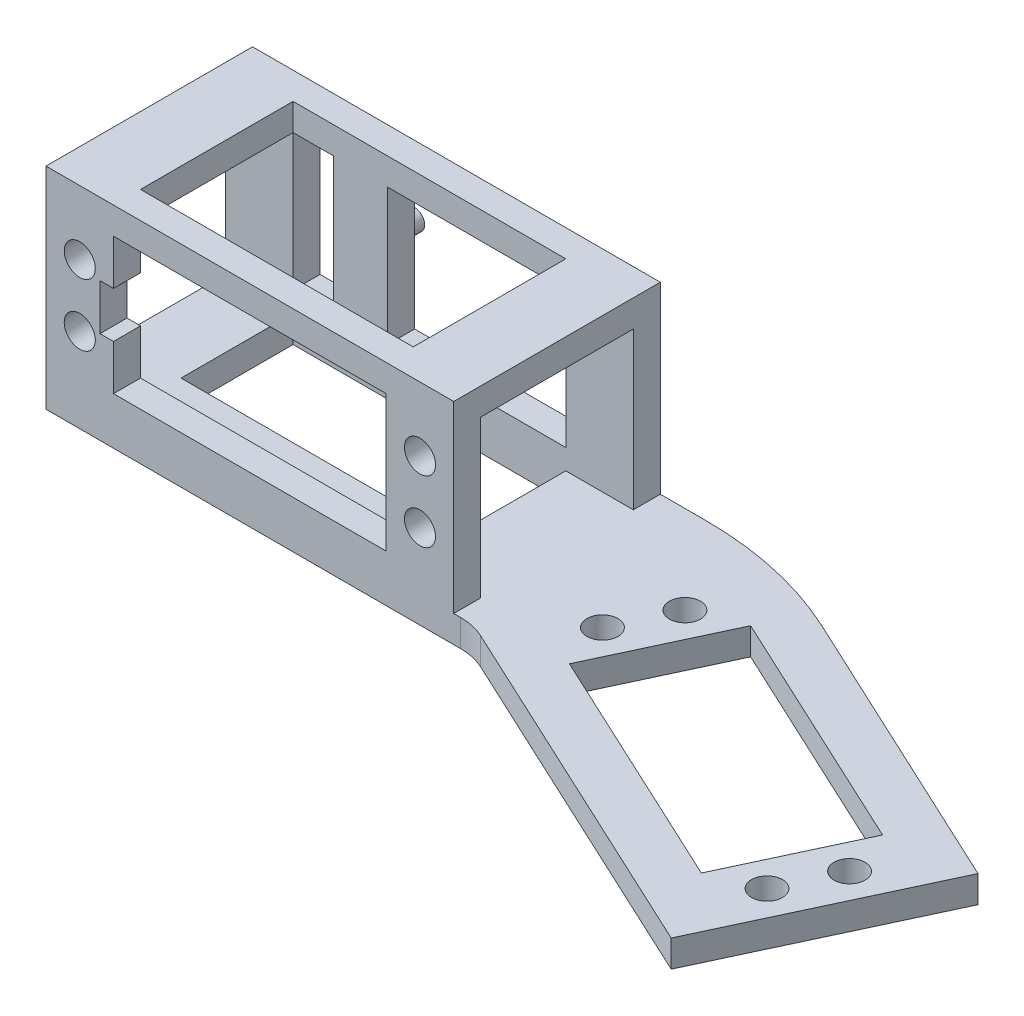
SolidWorks part; units mm, degrees
ref_plane "Płaszczyzna przednia" through (0, 0, 0) normal (0, 0, 1) x (1, 0, 0)
ref_plane "Płaszczyzna górna" through (0, 0, 0) normal (0, 1, 0) x (1, 0, 0)
ref_plane "Płaszczyzna prawa" through (0, 0, 0) normal (1, 0, 0) x (0, 0, -1)
sketch "Szkic1" plane through (0, 0, 0) normal (0, 0, 1) x (1, 0, 0)
  line L0 (17.1567, 10.1) -> (79.0535, 10.1) construction
  line L9 (-10, 27.2) -> (50.4, 27.2)
  line L10 (-10, 27.2) -> (-10, -7)
  line L11 (-10, -7) -> (50.4, -7)
  line L12 (50.4, 27.2) -> (50.4, -7)
  line L13 (20.2, 34.0981) -> (20.2, -18.6436) construction
extrude "Dodanie-wyciągnięcie1" add sketch "Szkic1" along normal blind 4
sketch "Szkic2" plane through (0, -7, 0) normal (0, -1, 0) x (1, 0, 0)
  line L1 (-10, 4) -> (-10, 0)
  line L2 (-10, 0) -> (-16.7213, 0)
  line L6 (50.4, 4) -> (50.4, 30.6)
  line L7 (50.4, 30.6) -> (-10, 30.6)
  line L9 (-10, 4) -> (50.4, 4) construction
  line L10 (-10, 4) -> (0, 4)
  line L11 (40.4, 4) -> (40.4, 20.6)
  line L12 (40.4, 20.6) -> (0, 20.6)
  line L13 (0, 20.6) -> (0, 4)
  line L14 (40.4, 4) -> (50.4, 4)
  line L16 (-38.789, 4.8923) -> (-82.1898, 25.1304)
  line L24 (50.4, 4) -> (50.4, 0) construction
  line L25 (-10, 30.6) -> (-11, 30.6)
  line L26 (-14.8036, 31.4432) -> (-67.7362, 56.1261)
  line L27 (-67.7362, 56.1261) -> (-82.1898, 25.1304)
  line L28 (-61.6315, 45.5558) -> (-70.1684, 27.2484)
  line L29 (-70.1684, 27.2484) -> (-33.5535, 10.1746)
  line L30 (-33.5535, 10.1746) -> (-25.0167, 28.482)
  line L31 (-25.0167, 28.482) -> (-61.6315, 45.5558)
  line L32 (-10, 4) -> (-10, 0) construction
  line L33 (-76.5626, 25.3669) -> (-59.3874, 62.1993) construction
  line L34 (-51.861, 18.7115) -> (-32.7873, 59.6151) construction
  line L35 (-65.8999, 36.4021) -> (-24.1196, 16.9196) construction
  arc A4 (-11, 30.6) -> (-14.8036, 31.4432) centre (-11, 39.6) cw
  arc A5 (-16.7213, 0) -> (-38.789, 4.8923) centre (-16.7213, 52.2167) cw
  circle A6 centre (-68.4874, 42.6842) radius 2.3
  circle A7 centre (-22.8095, 21.3842) radius 2.3
  circle A8 centre (-26.6976, 13.0462) radius 2.3
  circle A9 centre (-72.3755, 34.3462) radius 2.3
  point P37 (-12.9953, 30.6)
  dimension "D15" = 9
  dimension "D24" = 4.6
  dimension "D6" = 52.2167
  dimension "D1" = 10
  dimension "D2" = 10
  dimension "D3" = 10
  dimension "D4" = 26.6
  dimension "D16" = 60.4
  dimension "D17" = 7
  dimension "D18" = 7
  dimension "D19" = 40.4
  dimension "D20" = 10
  dimension "D21" = 65
  dimension "D22" = 1
  dimension "D23" = 5
  dimension "D25" = 5.5
  dimension "D26" = 20.2
extrude "Dodanie-wyciągnięcie2" add sketch "Szkic2" against normal blind 4
sketch "Szkic8" plane through (0, 0, 30.6) normal (0, 0, 1) x (1, 0, 0)
  line L0 (-9.6092, 10.1) -> (52.2876, 10.1) construction
  line L1 (0, 20.2) -> (40.4, 20.2)
  line L2 (0, 20.2) -> (0, 0)
  line L3 (0, 0) -> (40.4, 0)
  line L4 (40.4, 20.2) -> (40.4, 0)
  line L5 (-10, 25.2) -> (50.4, 25.2)
  line L6 (-10, 25.2) -> (-10, -7)
  line L7 (-10, -7) -> (50.4, -7)
  line L8 (50.4, 25.2) -> (50.4, -7)
  line L9 (20.2, 34.6544) -> (20.2, -18.0872) construction
  line L10 (50.4, -7) -> (-11, -7) construction
  line L11 (50.4, -3) -> (50.4, 27.2) construction
  circle A0 centre (-5, 14.7) radius 2.3
  circle A1 centre (-5, 5.5) radius 2.3
  circle A2 centre (45.4, 5.5) radius 2.3
  circle A3 centre (45.4, 14.7) radius 2.3
  point P29 (0, 10.1)
  point P31 (20.2, 20.2)
  dimension "D8" = 4.6
  dimension "D1" = 40.4
  dimension "D2" = 20.2
  dimension "D3" = 10
  dimension "D4" = 5
  dimension "D5" = 10
  dimension "D6" = 7
  dimension "D7" = 5.5
  dimension "D9" = 5
extrude "Dodanie-wyciągnięcie3" add sketch "Szkic8" against normal blind 4
sketch "Szkic10" plane through (0, 0, 0) normal (0, 0, -1) x (-1, 0, 0)
  line L0 (-47.6229, 10.1) -> (25.9546, 10.1) construction
  line L1 (-50.4, -7) -> (-50.4, 27.2) construction
  circle A0 centre (-30.4, 10.1) radius 1.5
  point P9 (-50.4, 10.1)
  dimension "D2" = 3
  dimension "D1" = 20
extrude "Dodanie-wyciągnięcie4" add sketch "Szkic10" along normal blind 4
sketch "Szkic11" plane through (0, 27.2, 0) normal (0, 1, 0) x (1, 0, 0)
  line L0 (50.4, -30.6) -> (-10, -30.6) construction
  line L1 (-10, 0) -> (0, 0)
  line L2 (-10, 0) -> (-10, -30.6)
  line L3 (-10, -30.6) -> (0, -30.6)
  line L4 (0, 0) -> (0, -30.6)
  line L6 (50.4, 0) -> (40.4, 0)
  line L7 (50.4, 0) -> (50.4, -30.6)
  line L8 (50.4, -30.6) -> (40.4, -30.6)
  line L9 (40.4, 0) -> (40.4, -30.6)
extrude "Dodanie-wyciągnięcie5" add sketch "Szkic11" against normal blind 5 from offset 2 offset against normal yes
sketch "Szkic12" plane through (0, 27.2, 0) normal (0, 1, 0) x (1, 0, 0)
  line L1 (-10, 0) -> (50.4, 0)
  line L2 (-10, 0) -> (-10, -4)
  line L4 (50.4, 0) -> (50.4, -4)
  line L6 (-10, -4) -> (-10, -30.6)
  line L7 (-10, -30.6) -> (50.4, -30.6)
  line L8 (50.4, -4) -> (50.4, -30.6)
extrude "Wytnij-wyciągnięcie1" cut sketch "Szkic12" against normal blind 3
sketch "Szkic13" plane through (0, 0, 0) normal (0, 0, -1) x (-1, 0, 0)
  line L0 (-40.4, 20.2) -> (0, 20.2) construction
  line L1 (-40.4, 0) -> (-40.4, 20.2) construction
  line L2 (0, 0) -> (-40.4, 0) construction
  line L3 (0, 20.2) -> (0, 0) construction
  line L4 (-40.4, 20.2) -> (-34.4, 20.2)
  line L5 (-40.4, 0) -> (-40.4, 20.2)
  line L6 (0, 0) -> (-26.4, 0)
  line L7 (0, 20.2) -> (0, 0)
  line L8 (-26.4, 20.2) -> (-26.4, 0)
  line L9 (-34.4, 20.2) -> (-34.4, 0)
  line L10 (-34.4, 0) -> (-40.4, 0)
  line L11 (-26.4, 20.2) -> (0, 20.2)
  circle A0 centre (-30.4, 10.1) radius 1.5 construction
  dimension "D1" = 4
  dimension "D2" = 4
extrude "Wytnij-wyciągnięcie2" cut sketch "Szkic13" against normal up to surface (4 mm away) up to face at (20.2, 8.6, 4)
mirror "Lustro1" about plane through (50.4, 27.2, 4) normal (-1, 0, 0) of bodies 113
delete or keep bodies "Obiekt-Usuń/zachowaj 1" type delete bodies bodies 113
sketch "Szkic14" plane through (0, 0, 30.6) normal (0, 0, 1) x (1, 0, 0)
  line L0 (60.4, 10.1) -> (47.0804, 10.1) construction
  line L1 (60.4, 0) -> (60.4, 20.2) construction
  line L2 (60.4, 13.5) -> (58.4, 13.5)
  line L3 (58.4, 13.5) -> (58.4, 6.7)
  line L4 (60.4, 6.7) -> (58.4, 6.7)
  line L5 (60.4, 6.7) -> (60.4, 13.5)
  point P8 (58.4, 10.1)
  dimension "D1" = 2
  dimension "D2" = 3.4
extrude "Wytnij-wyciągnięcie3" cut sketch "Szkic14" against normal up to next
